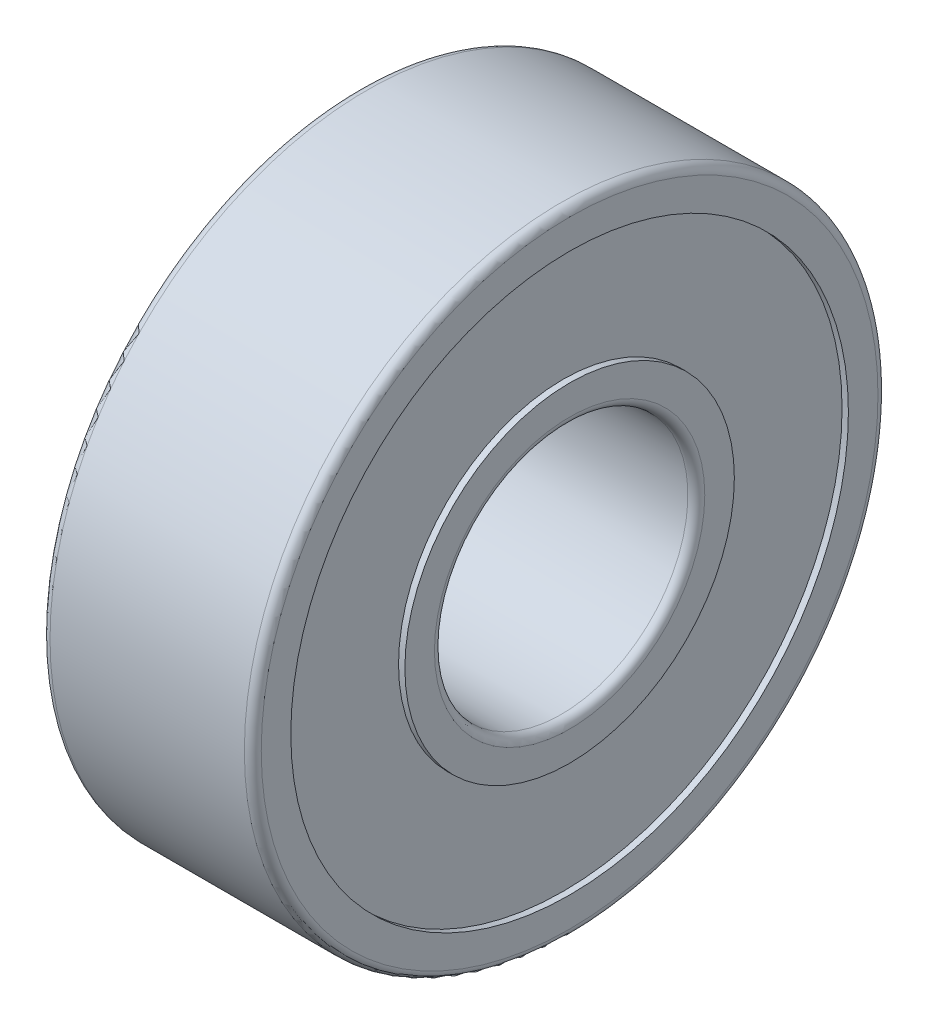
SolidWorks part; units mm, degrees
ref_plane "Front Plane" through (0, 0, 0) normal (0, 0, 1) x (1, 0, 0)
ref_plane "Top Plane" through (0, 0, 0) normal (0, 1, 0) x (1, 0, 0)
ref_plane "Right Plane" through (0, 0, 0) normal (1, 0, 0) x (0, 0, -1)
sketch "Sketch1" plane through (0, 0, 0) normal (0, 0, 1) x (1, 0, 0)
  line L0 (0, 0) -> (5, 0) construction
  line L1 (0, 3) -> (0, 3.9)
  line L2 (0, 3.9) -> (0.15, 3.9)
  line L3 (0.15, 3.9) -> (0.15, 6.6)
  line L4 (0.15, 6.6) -> (0, 6.6)
  line L5 (0, 6.6) -> (0, 7.5)
  line L6 (0, 7.5) -> (5, 7.5)
  line L7 (5, 7.5) -> (5, 6.6)
  line L8 (5, 6.6) -> (4.85, 6.6)
  line L9 (4.85, 6.6) -> (4.85, 3.9)
  line L10 (4.85, 3.9) -> (5, 3.9)
  line L11 (5, 3.9) -> (5, 3)
  line L12 (5, 3) -> (0, 3)
  dimension "D_s" = 6
  dimension "P" = 15
  dimension "B" = 5
  dimension "MSM_3" = 7.8
  dimension "MSM_4" = 13.2
  dimension "MSM_5" = 4.7
revolve "Revolve1" add sketch "Sketch1" angle 360 about L0
fillet "Fillet1" radius 0.2 4 edges at (0, 0, 3) (5, 0, 3) (0, 0, 7.5) (5, 0, 7.5)
